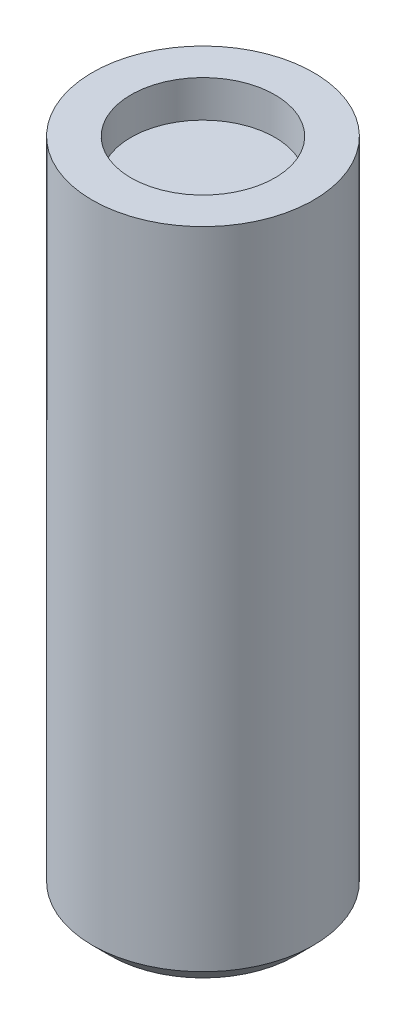
SolidWorks part; units mm, degrees
ref_plane "Front Plane" through (0, 0, 0) normal (0, 0, 1) x (1, 0, 0)
ref_plane "Top Plane" through (0, 0, 0) normal (0, 1, 0) x (1, 0, 0)
ref_plane "Right Plane" through (0, 0, 0) normal (1, 0, 0) x (0, 0, -1)
sketch "Sketch1" plane through (0, 0, 0) normal (0, 1, 0) x (1, 0, 0)
  circle A0 centre (0, 0) radius 0.6
  dimension "D1" = 1.2
extrude "Boss-Extrude1" add sketch "Sketch1" along normal blind 3.6
chamfer "Chamfer1" distance 0.1 angle 45 1 edges at (0, 0, 0.6)
sketch "Sketch2" plane through (0, 3.6, 0) normal (0, 1, 0) x (1, 0, 0)
  circle A0 centre (0, 0) radius 0.3905
extrude "Cut-Extrude1" cut sketch "Sketch2" against normal blind 0.2
